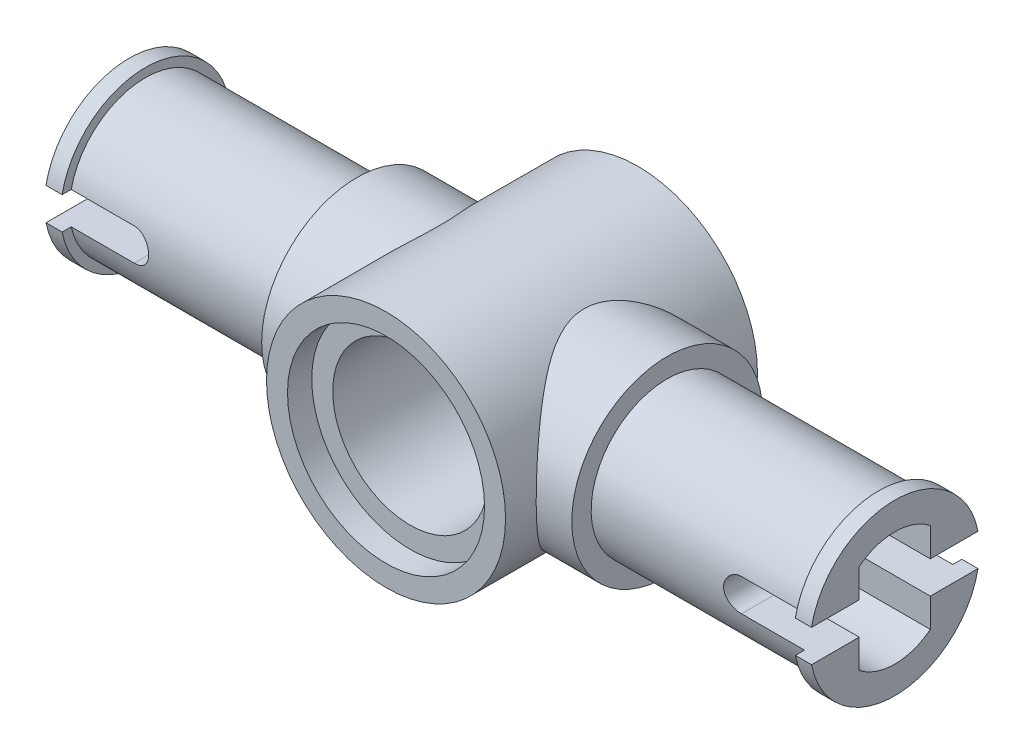
SolidWorks part; units mm, degrees
ref_plane "Front Plane" through (0, 0, 0) normal (0, 0, 1) x (1, 0, 0)
ref_plane "Top Plane" through (0, 0, 0) normal (0, 1, 0) x (1, 0, 0)
ref_plane "Right Plane" through (0, 0, 0) normal (1, 0, 0) x (0, 0, -1)
sketch "Sketch1" plane through (0, 0, 0) normal (1, 0, 0) x (0, 0, -1)
  circle A0 centre (0, 0) radius 2.35
  dimension "D1" = 4.7
extrude "Pin" add sketch "Sketch1" along normal mid plane 22.7
sketch "Sketch2" plane through (0, 0, 0) normal (1, 0, 0) x (0, 0, -1)
  circle A0 centre (0, 0) radius 2.95
  dimension "D1" = 5.9
extrude "Middle " add sketch "Sketch2" along normal mid plane 9.6
sketch "Sketch3" plane through (11.35, 0, 0) normal (1, 0, 0) x (0, 0, -1)
  circle A0 centre (0, 0) radius 2.625
  dimension "D1" = 5.25
extrude "Outer Rim" add sketch "Sketch3" along normal blind 0.5
mirror "Mirror1" about plane through (0, 0, 0) normal (1, 0, 0) of "Outer Rim"
sketch "Sketch4" plane through (0, 0, 0) normal (1, 0, 0) x (0, 0, -1)
  line L1 (1.1, -2.3834) -> (-1.1, -2.3834)
  line L2 (1.1, -2.3834) -> (1.1, 2.3834)
  line L3 (1.1, 2.3834) -> (-1.1, 2.3834)
  line L4 (-1.1, -2.3834) -> (-1.1, 2.3834)
  line L5 (1.1, -2.3834) -> (-1.1, 2.3834) construction
  line L6 (1.1, 2.3834) -> (-1.1, -2.3834) construction
  circle A1 centre (0, 0) radius 2.625 construction
  circle A2 centre (0, 0) radius 1.775
  circle A3 centre (0, 0) radius 1.775
  point P7 (1.1, 2.3834)
  dimension "D2" = 2.2
  dimension "D1" = 0.85
extrude "Bore Cut " cut sketch "Sketch4" against normal through all both and the other way through all contours L2 A3 L4
sketch "Sketch5" plane through (0, 0, 0) normal (0, 0, 1) x (1, 0, 0)
  line L0 (14.3, 0) -> (9.4, 0) construction
  line L1 (11.85, -2.625) -> (11.85, 2.625) construction
  line L2 (14.3, -0.5) -> (9.4, -0.5)
  line L3 (14.3, 0.5) -> (9.4, 0.5)
  line L4 (0, 0) -> (0, 5.0044) construction
  line L5 (-14.3, 0) -> (-9.4, 0) construction
  line L6 (-14.3, -0.5) -> (-9.4, -0.5)
  line L7 (-14.3, 0.5) -> (-9.4, 0.5)
  arc A0 (14.3, -0.5) -> (14.3, 0.5) centre (14.3, 0) ccw
  arc A1 (9.4, 0.5) -> (9.4, -0.5) centre (9.4, 0) ccw
  arc A2 (-14.3, -0.5) -> (-14.3, 0.5) centre (-14.3, 0) cw
  arc A3 (-9.4, 0.5) -> (-9.4, -0.5) centre (-9.4, 0) cw
  point P5 (11.85, 0)
  point P14 (-11.85, 0)
  dimension "D2" = 17.8
  dimension "D1" = 1
extrude "Slot Cut " cut sketch "Sketch5" against normal through all both and the other way through all
sketch "Sketch6" plane through (0, 0, 0) normal (0, 0, 1) x (1, 0, 0)
  circle A0 centre (0, 0) radius 3.7
  dimension "D1" = 7.4
extrude "Middle Body" add sketch "Sketch6" along normal mid plane 7.8
sketch "Sketch7" plane through (0, 0, 0) normal (0, 0, 1) x (1, 0, 0)
  circle A0 centre (0, 0) radius 2.4
  dimension "D1" = 4.8
extrude "Middle Bore " cut sketch "Sketch7" against normal through all both and the other way through all
sketch "Sketch8" plane through (0, 0, 3.9) normal (0, 0, 1) x (1, 0, 0)
  circle A0 centre (0, 0) radius 3.05
  dimension "D1" = 6.1
extrude "Middle Rim Cut " cut sketch "Sketch8" against normal blind 0.75
mirror "Mirror2" about plane through (0, 0, 0) normal (0, 0, 1) of "Middle Rim Cut "
